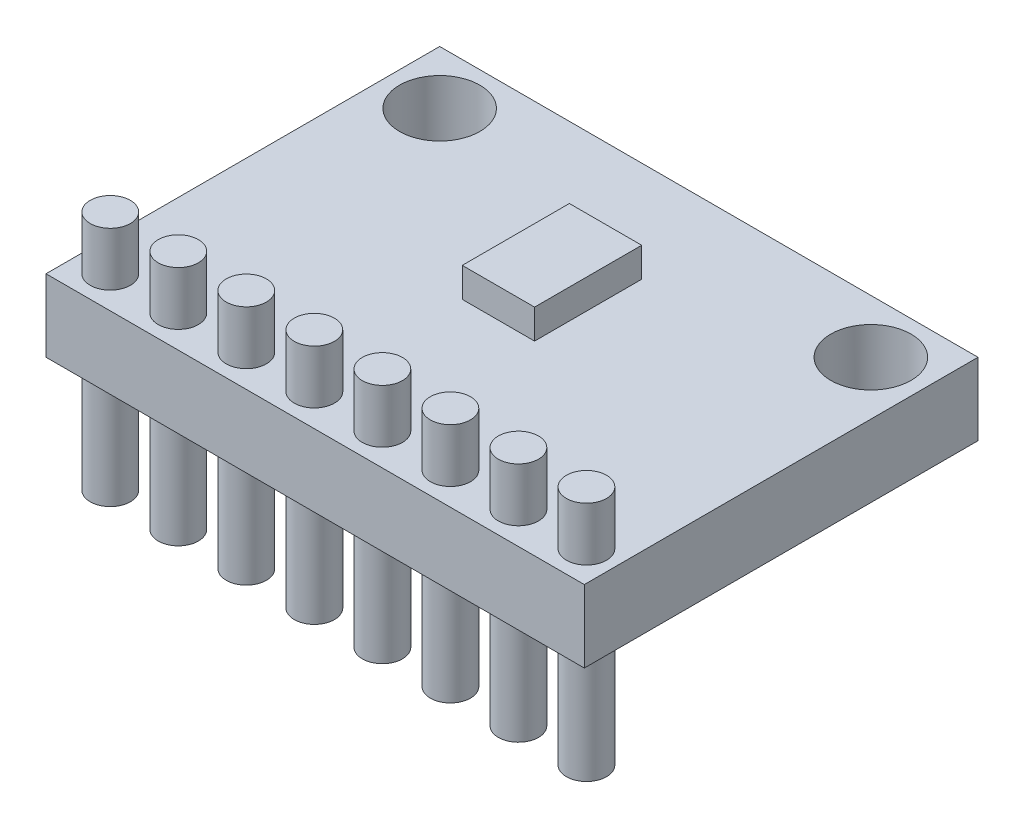
SolidWorks part; units mm, degrees
ref_plane "Front Plane" through (0, 0, 0) normal (0, 0, 1) x (1, 0, 0)
ref_plane "Top Plane" through (0, 0, 0) normal (0, 1, 0) x (1, 0, 0)
ref_plane "Right Plane" through (0, 0, 0) normal (1, 0, 0) x (0, 0, -1)
sketch "Sketch1" plane through (0, 0, 0) normal (0, 1, 0) x (1, 0, 0)
  line L1 (10.05, -7.35) -> (-10.05, -7.35)
  line L2 (10.05, -7.35) -> (10.05, 7.35)
  line L3 (10.05, 7.35) -> (-10.05, 7.35)
  line L4 (-10.05, -7.35) -> (-10.05, 7.35)
  line L5 (10.05, -7.35) -> (-10.05, 7.35) construction
  line L6 (10.05, 7.35) -> (-10.05, -7.35) construction
  point P1 (0, 0)
  dimension "D1" = 14.7
  dimension "D2" = 20.1
extrude "Boss-Extrude1" add sketch "Sketch1" along normal blind 2.7
sketch "Sketch2" plane through (0, 2.7, 0) normal (0, 1, 0) x (1, 0, 0)
  line L0 (-10.05, 7.35) -> (-10.05, -7.35) construction
  line L1 (10.05, -7.35) -> (10.05, 7.35) construction
  line L2 (-10.05, -7.35) -> (10.05, -7.35) construction
  circle A0 centre (-8.85, -6.15) radius 0.75
  circle A1 centre (-6.31, -6.15) radius 0.75
  circle A2 centre (-3.77, -6.15) radius 0.75
  circle A3 centre (-1.23, -6.15) radius 0.75
  circle A4 centre (1.31, -6.15) radius 0.75
  circle A5 centre (3.85, -6.15) radius 0.75
  circle A6 centre (6.39, -6.15) radius 0.75
  circle A7 centre (8.93, -6.15) radius 0.75
  dimension "D1" = 1.5
  dimension "D4" = 1.12
  dimension "D3" = 1.2
  dimension "D5" = 1.2
  dimension "D2" = 8
extrude "Boss-Extrude2" add sketch "Sketch2" along normal blind 2 and the other way blind 7
sketch "Sketch3" plane through (0, 2.7, 0) normal (0, 1, 0) x (1, 0, 0)
  line L0 (-10.05, 7.35) -> (-10.05, -7.35) construction
  line L1 (10.05, 7.35) -> (-10.05, 7.35) construction
  line L2 (0, -10.2504) -> (0, 12.3114) construction
  circle A0 centre (-8.05, 5.35) radius 1.5
  circle A1 centre (8.05, 5.35) radius 1.5
  dimension "D1" = 3
  dimension "D2" = 2
  dimension "D3" = 2
extrude "Cut-Extrude1" cut sketch "Sketch3" against normal through all
sketch "Sketch4" plane through (0, 2.7, 0) normal (0, 1, 0) x (1, 0, 0)
  line L1 (1.2492, 3.5932) -> (-1.4508, 3.5932)
  line L2 (1.2492, 3.5932) -> (1.2492, -0.4068)
  line L3 (1.2492, -0.4068) -> (-1.4508, -0.4068)
  line L4 (-1.4508, 3.5932) -> (-1.4508, -0.4068)
  line L5 (1.2492, 3.5932) -> (-1.4508, -0.4068) construction
  line L6 (1.2492, -0.4068) -> (-1.4508, 3.5932) construction
  point P0 (-0.1008, 1.5932)
  dimension "D1" = 2.7
  dimension "D2" = 4
extrude "Boss-Extrude3" add sketch "Sketch4" along normal blind 1.1
